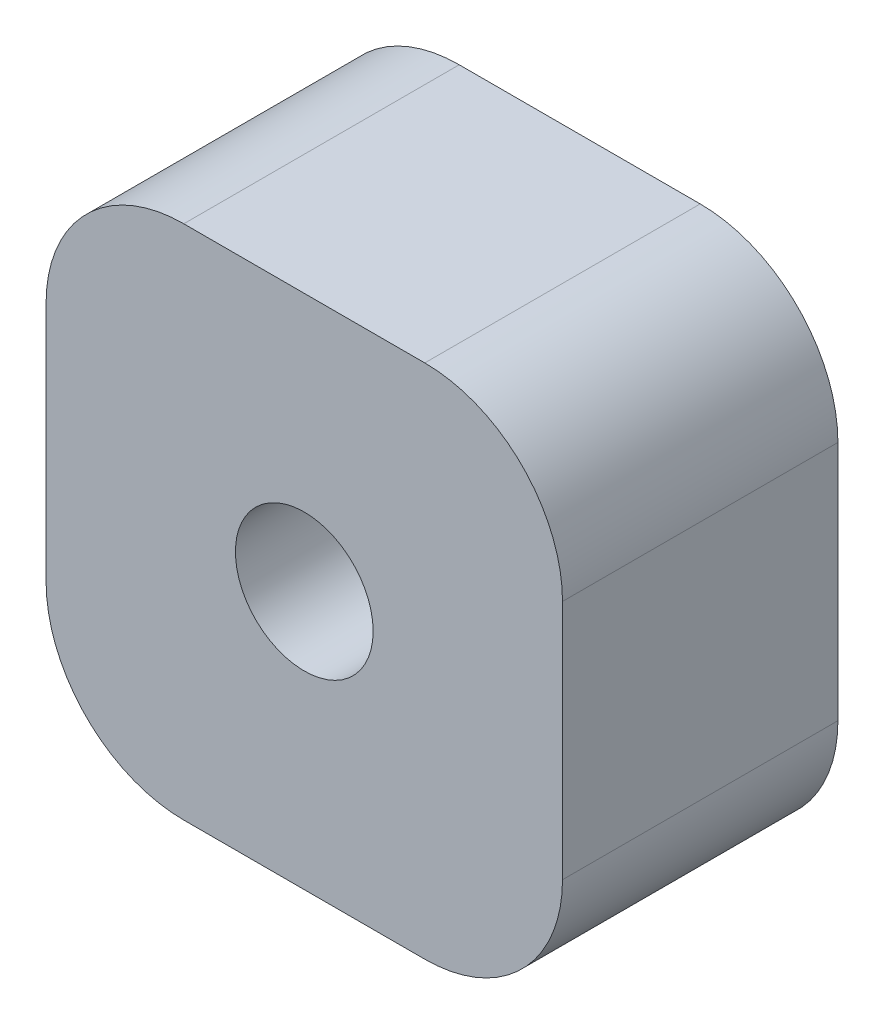
SolidWorks part; units mm, degrees
material "PLA"
ref_plane "前视基准面" through (0, 0, 0) normal (0, 0, 1) x (1, 0, 0)
ref_plane "上视基准面" through (0, 0, 0) normal (0, 1, 0) x (1, 0, 0)
ref_plane "右视基准面" through (0, 0, 0) normal (1, 0, 0) x (0, 0, -1)
sketch "草图1" plane through (0, 0, 0) normal (0, 0, 1) x (1, 0, 0)
  line L0 (0, 15.9868) -> (0, -14.4572) construction
  line L1 (-7.5, -7.5) -> (7.5, -7.5)
  line L2 (-7.5, -7.5) -> (-7.5, 7.5)
  line L3 (-7.5, 7.5) -> (7.5, 7.5)
  line L4 (7.5, -7.5) -> (7.5, 7.5)
  line L5 (-7.5, -7.5) -> (7.5, 7.5) construction
  line L6 (-7.5, 7.5) -> (7.5, -7.5) construction
  line L7 (-19.1941, 0) -> (21.5625, 0) construction
  circle A0 centre (0, 0) radius 2
  point P0 (0, 0)
  dimension "D3" = 4
  dimension "D1" = 15
  dimension "D2" = 15
extrude "凸台-拉伸1" add sketch "草图1" along normal blind 8
fillet "圆角1" radius 4 4 edges at (7.5, -7.5, 4) (7.5, 7.5, 4) (-7.5, 7.5, 4) (-7.5, -7.5, 4)
